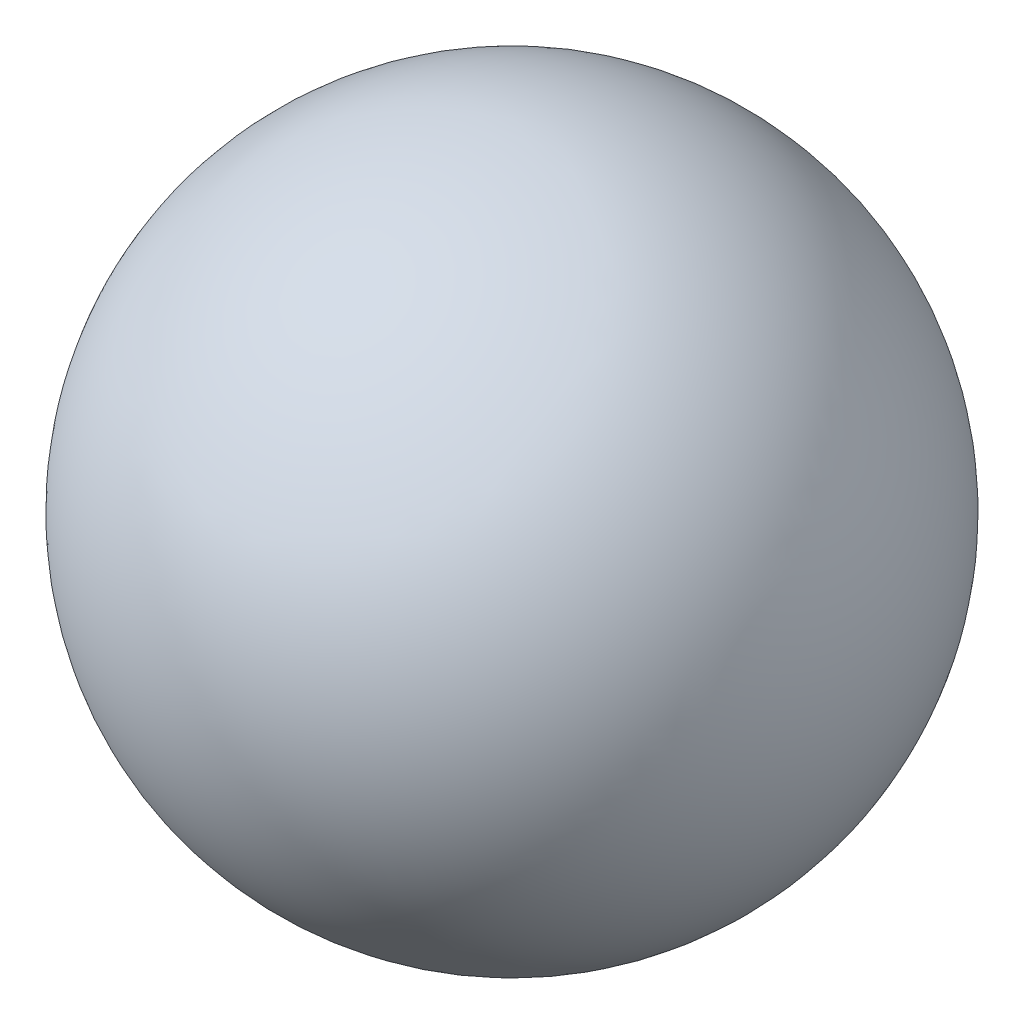
SolidWorks part; units mm, degrees
ref_plane "Ebene vorne" through (0, 0, 0) normal (0, 0, 1) x (1, 0, 0)
ref_plane "Ebene oben" through (0, 0, 0) normal (0, 1, 0) x (1, 0, 0)
ref_plane "Ebene rechts" through (0, 0, 0) normal (1, 0, 0) x (0, 0, -1)
sketch "Skizze1" plane through (0, 0, 0) normal (0, 0, 1) x (1, 0, 0)
  line L0 (0, 0) -> (43.8137, 0) construction
  line L1 (-2.5981, 1.5) -> (0.4019, 1.5)
  line L2 (0.4019, 1.5) -> (1.1995, 0)
  line L3 (0, 0) -> (-8.8359, 0) construction
  line L4 (3, 0) -> (1.1995, 0)
  arc A0 (3, 0) -> (-2.5981, 1.5) centre (0, 0) ccw
  dimension "D1" = 6
  dimension "D2" = 3
  dimension "D3" = 118
  dimension "D4" = 1.5
revolve "Rotation1" add sketch "Skizze1" angle 360 about L3
